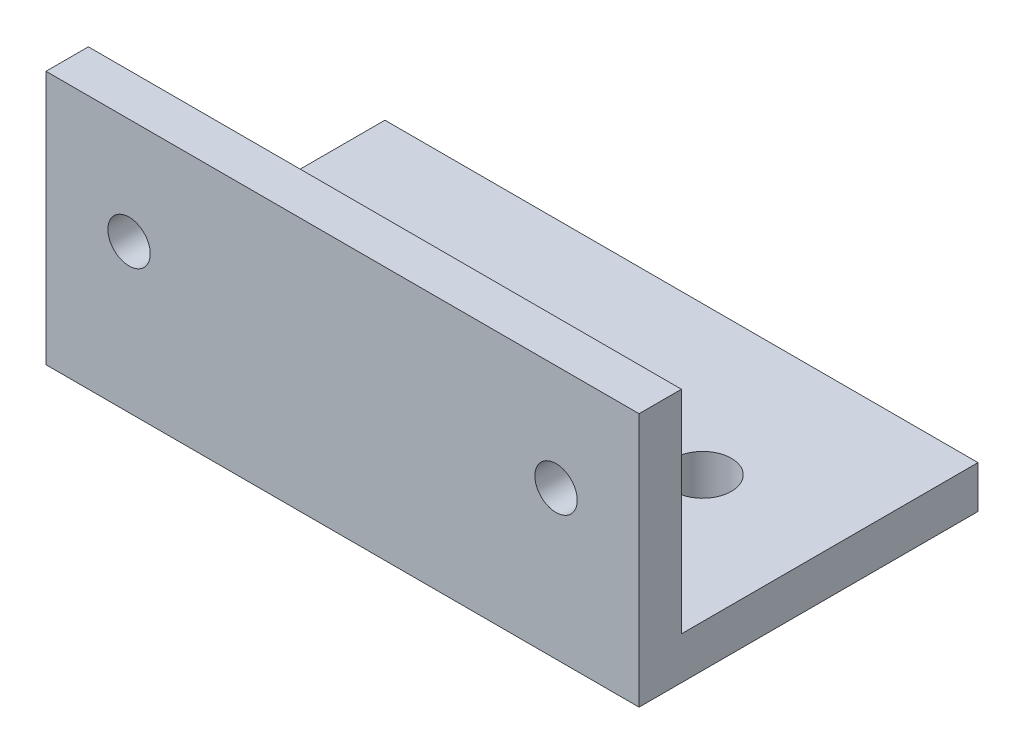
SolidWorks part; units mm, degrees
material "6061-T6 (SS)"
ref_plane "Front Plane" through (0, 0, 0) normal (0, 0, 1) x (1, 0, 0)
ref_plane "Top Plane" through (0, 0, 0) normal (0, 1, 0) x (1, 0, 0)
ref_plane "Right Plane" through (0, 0, 0) normal (1, 0, 0) x (0, 0, -1)
sketch "Sketch1" plane through (0, 0, 0) normal (1, 0, 0) x (0, 0, -1)
  line L0 (0, 19.05) -> (0, 0)
  line L1 (0, 0) -> (25.4, 0)
  line L2 (25.4, 0) -> (25.4, 3.175)
  line L3 (25.4, 3.175) -> (3.175, 3.175)
  line L4 (3.175, 3.175) -> (3.175, 19.05)
  line L5 (3.175, 19.05) -> (0, 19.05)
  dimension "D1" = 25.4
  dimension "D2" = 19.05
  dimension "D3" = 3.175
extrude "Boss-Extrude1" add sketch "Sketch1" along normal blind 44.45
sketch "Sketch3" plane through (0, 0, -3.175) normal (0, 0, -1) x (-1, 0, 0)
  line L0 (-22.225, 3.175) -> (-22.225, 19.05) construction
  line L1 (-44.45, 3.175) -> (0, 3.175) construction
  line L2 (-44.45, 19.05) -> (0, 19.05) construction
  line L3 (-38.225, 11.1125) -> (-6.225, 11.1125) construction
  circle A0 centre (-38.225, 11.1125) radius 1.5875
  circle A1 centre (-6.225, 11.1125) radius 1.5875
  point P9 (-22.225, 11.1125)
  dimension "D2" = 3.175
  dimension "D1" = 32
extrude "Cut-Extrude1" cut sketch "Sketch3" against normal blind 25.4
sketch "Sketch4" plane through (0, 3.175, 0) normal (0, 1, 0) x (1, 0, 0)
  line L0 (0, 14.2875) -> (44.45, 14.2875) construction
  line L1 (0, 25.4) -> (0, 3.175) construction
  line L3 (34.925, 14.2875) -> (9.525, 14.2875)
  circle A0 centre (9.525, 14.2875) radius 2.1526
  circle A1 centre (34.925, 14.2875) radius 2.1527
  point P13 (22.225, 14.2875)
  dimension "D1" = 4.3053
  dimension "D2" = 25.4
extrude "Cut-Extrude2" cut sketch "Sketch4" against normal blind 25.4 contours L0 L3 A1 | L3 L0 A1 | A0 L0 L3 | L0 A0 L3
